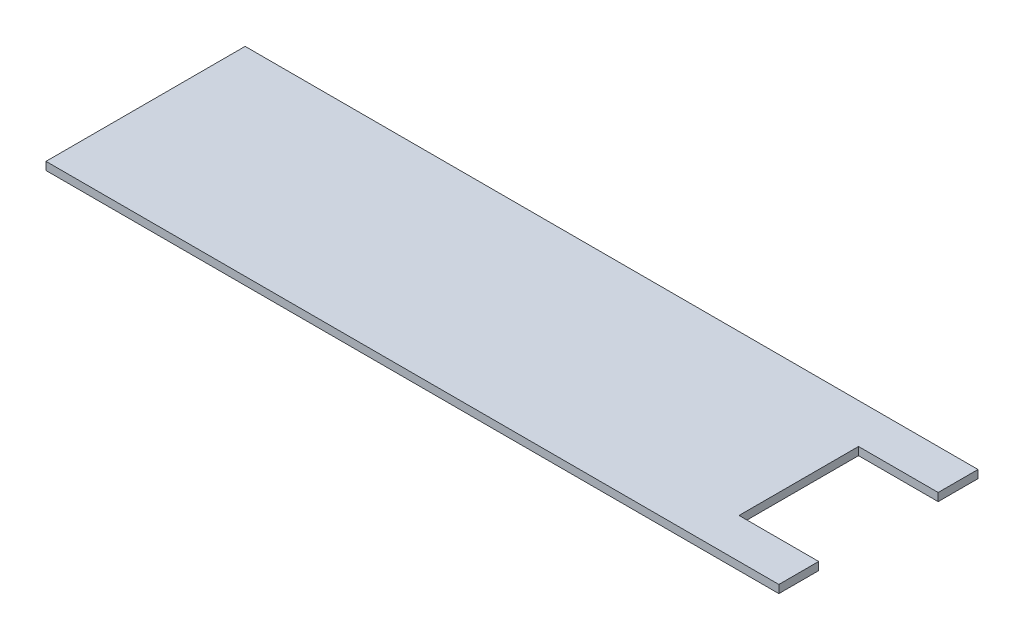
SolidWorks part; units mm, degrees
ref_plane "前视基准面" through (0, 0, 0) normal (0, 0, 1) x (1, 0, 0)
ref_plane "上视基准面" through (0, 0, 0) normal (0, 1, 0) x (1, 0, 0)
ref_plane "右视基准面" through (0, 0, 0) normal (1, 0, 0) x (0, 0, -1)
sketch "草图1" plane through (0, 0, 0) normal (0, 1, 0) x (1, 0, 0)
  line L1 (-54.4038, 14.1346) -> (37.5962, 14.1346)
  line L2 (-54.4038, 14.1346) -> (-54.4038, -10.8654)
  line L3 (-54.4038, -10.8654) -> (37.5962, -10.8654)
  line L4 (37.5962, 14.1346) -> (37.5962, -10.8654)
  line L5 (-54.4038, 14.1346) -> (37.5962, -10.8654) construction
  line L6 (-54.4038, -10.8654) -> (37.5962, 14.1346) construction
  point P4 (-8.4038, 1.6346)
  dimension "D1" = 25
  dimension "D2" = 92
extrude "凸台-拉伸1" add sketch "草图1" along normal blind 1
sketch "草图2" plane through (0, 1, 0) normal (0, 1, 0) x (1, 0, 0)
  line L0 (37.5962, -10.8654) -> (37.5962, 14.1346) construction
  line L2 (27.5962, 9.1346) -> (37.5962, 9.1346)
  line L3 (27.5962, 9.1346) -> (27.5962, -5.8654)
  line L4 (27.5962, -5.8654) -> (37.5962, -5.8654)
  line L5 (37.5962, 9.1346) -> (37.5962, -5.8654)
  line L6 (27.5962, 9.1346) -> (37.5962, -5.8654) construction
  line L7 (27.5962, -5.8654) -> (37.5962, 9.1346) construction
  point P0 (37.5962, 1.6346)
  point P7 (32.5962, 1.6346)
  point P8 (37.5962, 1.6346)
  point P9 (0, 0)
  dimension "D1" = 15
  dimension "D2" = 10
extrude "切除-拉伸1" cut sketch "草图2" against normal blind 1
